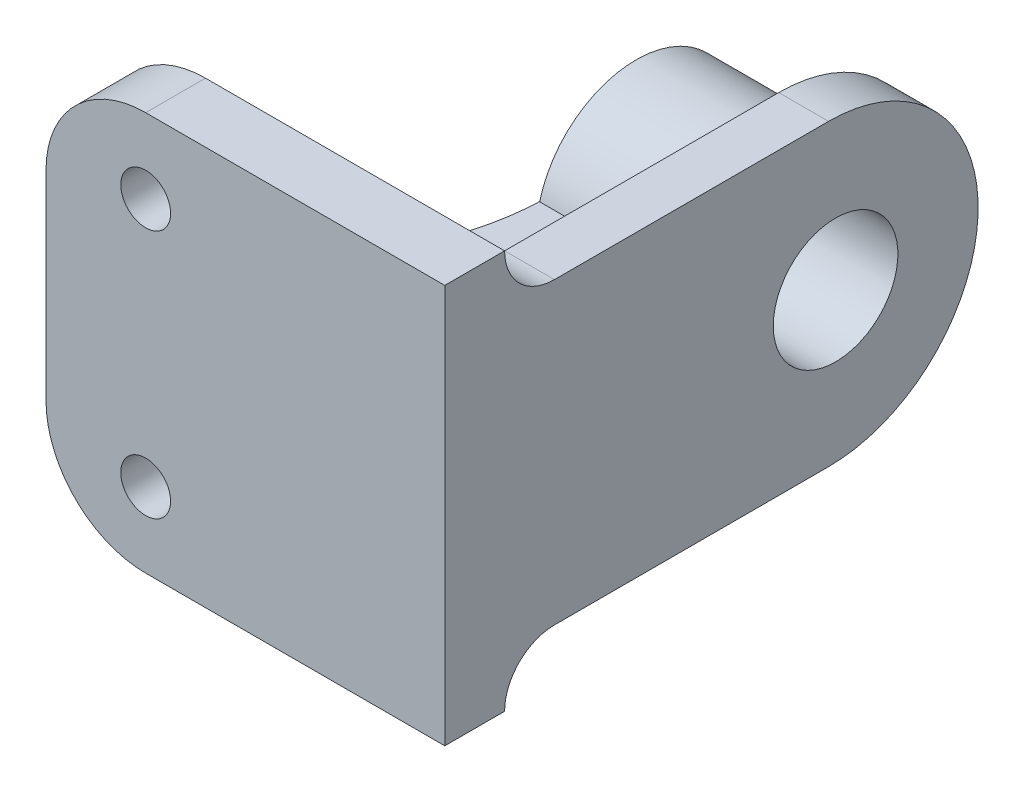
SolidWorks part; units mm, degrees
ref_plane "Front Plane" through (0, 0, 0) normal (0, 0, 1) x (1, 0, 0)
ref_plane "Top Plane" through (0, 0, 0) normal (0, 1, 0) x (1, 0, 0)
ref_plane "Right Plane" through (0, 0, 0) normal (1, 0, 0) x (0, 0, -1)
sketch "Sketch1" plane through (0, 0, 0) normal (0, 0, 1) x (1, 0, 0)
  line L1 (20, 0) -> (80, 0)
  line L2 (0, 20) -> (0, 60)
  line L3 (20, 80) -> (80, 80)
  line L4 (80, 0) -> (80, 80)
  arc A0 (20, 80) -> (0, 60) centre (20, 60) ccw
  arc A1 (0, 20) -> (20, 0) centre (20, 20) ccw
  dimension "D3" = 20
  dimension "D1" = 20
  dimension "D2" = 80
extrude "Boss-Extrude1" add sketch "Sketch1" along normal blind 12
sketch "Sketch2" plane through (0, 0, 12) normal (0, 0, 1) x (1, 0, 0)
  line L0 (0, 60) -> (0, 20) construction
  line L1 (20, 0) -> (80, 0) construction
  circle A0 centre (20, 65) radius 5
  circle A1 centre (20, 15) radius 5
  dimension "D1" = 10
  dimension "D2" = 10
  dimension "D3" = 50
  dimension "D4" = 20
  dimension "D5" = 15
  dimension "D6" = 15
extrude "Cut-Extrude1" cut sketch "Sketch2" against normal up to next
sketch "Sketch5" plane through (80, 0, 0) normal (1, 0, 0) x (0, 0, -1)
  line L0 (10, 70) -> (65, 70)
  line L1 (0, 0) -> (0, 80) construction
  line L2 (-12, 80) -> (0, 80) construction
  line L3 (65, 10) -> (10, 10)
  line L8 (0, 0) -> (0, 80)
  line L9 (0, 80) -> (-12, 80)
  line L10 (-12, 80) -> (-12, 0)
  line L11 (-12, 0) -> (0, 0)
  line L12 (0, 0) -> (0, 80)
  arc A0 (0, 80) -> (10, 70) centre (10, 80) ccw
  arc A1 (10, 10) -> (0, 0) centre (10, 0) ccw
  arc A2 (65, 70) -> (65, 10) centre (65, 40) cw
  dimension "D3" = 65
  dimension "D1" = 60
  dimension "D2" = 10
  dimension "D4" = 0
extrude "Boss-Extrude2" add sketch "Sketch5" against normal blind 10
sketch "Sketch8" plane through (70, 0, 0) normal (-1, 0, 0) x (0, 0, 1)
  circle A0 centre (-66.3989, 40) radius 20
  dimension "D1" = 40
extrude "Boss-Extrude3" add sketch "Sketch8" along normal blind 30
sketch "Sketch9" plane through (40, 0, 0) normal (-1, 0, 0) x (0, 0, 1)
  circle A0 centre (-66.3989, 40) radius 12.5
  circle A1 centre (-66.3989, 40) radius 20 construction
  dimension "D2" = 25
  dimension "D1" = 0
extrude "Cut-Extrude2" cut sketch "Sketch9" against normal up to next
sketch "Sketch12" plane through (0, 0, 0) normal (0, 0, -1) x (-1, 0, 0)
  line L0 (0, 40) -> (-40, 40)
  line L1 (0, 60) -> (0, 20) construction
  line L2 (-40, 20) -> (-40, 60) construction
  line L3 (-40, 40) -> (-70, 40)
  line L4 (-70, 80) -> (-70, 0) construction
sketch "Sketch13" plane through (70, 0, 0) normal (-1, 0, 0) x (0, 0, 1)
  line L0 (0, 40) -> (-52.7203, 40)
ref_plane "Plane1" through (0, 40, 0) normal (0, 1, 0) x (1, 0, 0)
sketch "Sketch16" plane through (0, 40, 0) normal (0, 1, 0) x (1, 0, 0)
  line L0 (40, 48.2193) -> (70, 48.2193)
  line L1 (40, 86.3989) -> (40, 46.3989) construction
  line L2 (70, 0) -> (70, 52.7203) construction
  line L3 (70, 48.2193) -> (70, 0)
  line L4 (70, 0) -> (0, 0)
  arc A0 (0, 0) -> (40, 48.2193) centre (-9.994, 48.991) ccw
  dimension "D1" = 100
extrude "Boss-Extrude4" add sketch "Sketch16" along normal mid plane 10
